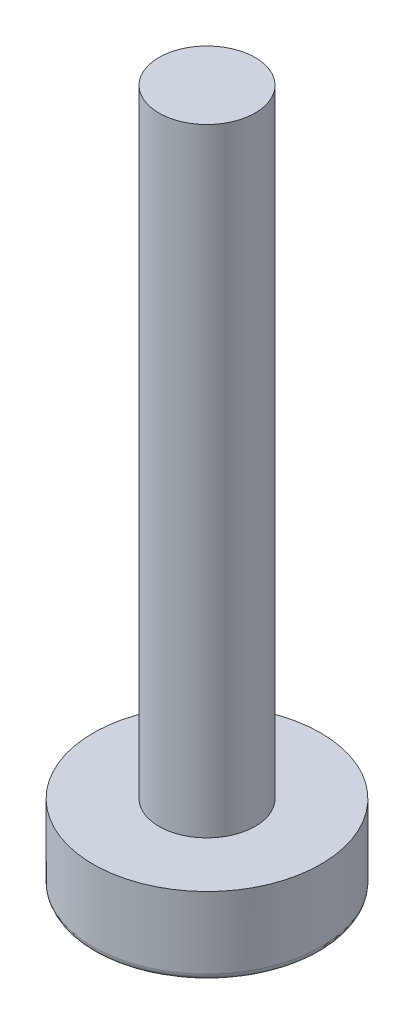
SolidWorks part; units mm, degrees
material "ABS"
ref_plane "Front Plane" through (0, 0, 0) normal (0, 0, 1) x (1, 0, 0)
ref_plane "Top Plane" through (0, 0, 0) normal (0, 1, 0) x (1, 0, 0)
ref_plane "Right Plane" through (0, 0, 0) normal (1, 0, 0) x (0, 0, -1)
sketch "Sketch1" plane through (0, 0, 0) normal (0, 1, 0) x (1, 0, 0)
  circle A0 centre (0, 0) radius 4.445
  dimension "D1" = 8.89
extrude "Boss-Extrude1" add sketch "Sketch1" along normal blind 3.048
sketch "Sketch2" plane through (0, 3.048, 0) normal (0, 1, 0) x (1, 0, 0)
  circle A0 centre (0, 0) radius 1.8796
  dimension "D1" = 3.7592
extrude "Boss-Extrude2" add sketch "Sketch2" along normal blind 24.13
fillet "Fillet1" radius 0.254 1 edges at (0, 0, 4.445)
